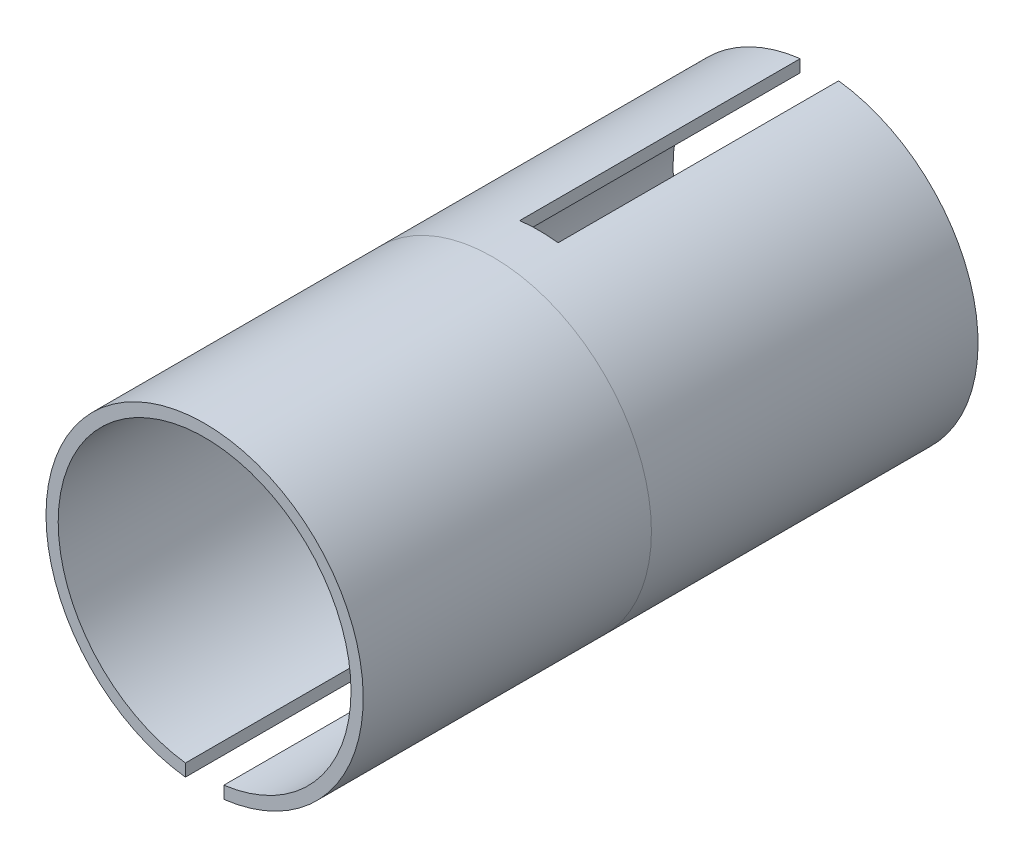
SolidWorks part; units mm, degrees
ref_plane "Front Plane" through (0, 0, 0) normal (0, 0, 1) x (1, 0, 0)
ref_plane "Top Plane" through (0, 0, 0) normal (0, 1, 0) x (1, 0, 0)
ref_plane "Right Plane" through (0, 0, 0) normal (1, 0, 0) x (0, 0, -1)
sketch "Sketch1" plane through (0, 0, 0) normal (0, 0, 1) x (1, 0, 0)
  circle A0 centre (0, 0) radius 38.1
  circle A1 centre (0, 0) radius 41.275
  dimension "D1" = 76.2
  dimension "D2" = 82.55
extrude "Boss-Extrude1" add sketch "Sketch1" along normal blind 160
sketch "Sketch2" plane through (0, 0, 0) normal (0, 1, 0) x (1, 0, 0)
  line L0 (-41.275, -160) -> (41.275, -160) construction
  line L1 (5, -220) -> (-5, -220) construction
  line L2 (5, -220) -> (5, -100) construction
  line L3 (5, -100) -> (-5, -100) construction
  line L4 (-5, -220) -> (-5, -100) construction
  line L5 (5, -220) -> (-5, -100) construction
  line L6 (5, -100) -> (-5, -220) construction
  line L7 (-5, -160) -> (5, -160)
  line L8 (5, -160) -> (5, -100)
  line L9 (-5, -100) -> (-5, -160)
  line L10 (-5, -100) -> (5, -100)
  point P0 (0, -160)
  dimension "D1" = 60
  dimension "D2" = 10
extrude "Cut-Extrude1" cut sketch "Sketch2" against normal blind 50
sketch "Sketch3" plane through (0, 0, 0) normal (0, 1, 0) x (1, 0, 0)
  line L0 (-41.275, -160) -> (41.275, -160) construction
  line L1 (-5, -277) -> (5, -277)
  line L2 (-5, -277) -> (-5, -160) construction
  line L4 (5, -277) -> (5, -160) construction
  line L5 (-5, -277) -> (0, -160) construction
  line L6 (-5, -43) -> (-3.7179, -73) construction
  line L7 (-5, -160) -> (5, -160)
  line L8 (5, -73) -> (5, -43)
  line L9 (-5, -43) -> (-5, -73)
  line L10 (38.1, 0) -> (-38.1, 0) construction
  line L11 (-5, -73) -> (5, -73)
  line L12 (-5, -73) -> (-5, 0)
  line L13 (-5, 0) -> (5, 0)
  line L14 (5, -73) -> (5, 0)
  line L15 (-5, -73) -> (-5, -43) construction
  line L16 (0, -160) -> (5, -277) construction
  line L17 (3.7179, -73) -> (5, -43) construction
  line L18 (5, -73) -> (5, -43) construction
  point P0 (0, -160)
  dimension "D1" = 117
  dimension "D2" = 10
extrude "Cut-Extrude2" cut sketch "Sketch3" along normal blind 50
ref_plane "Plane1" through (0, 0, 85) normal (0, 0, -1) x (-1, 0, 0)
split "Split1" trim tools "Plane1" bodies to split 103 resulting bodies 104 105
